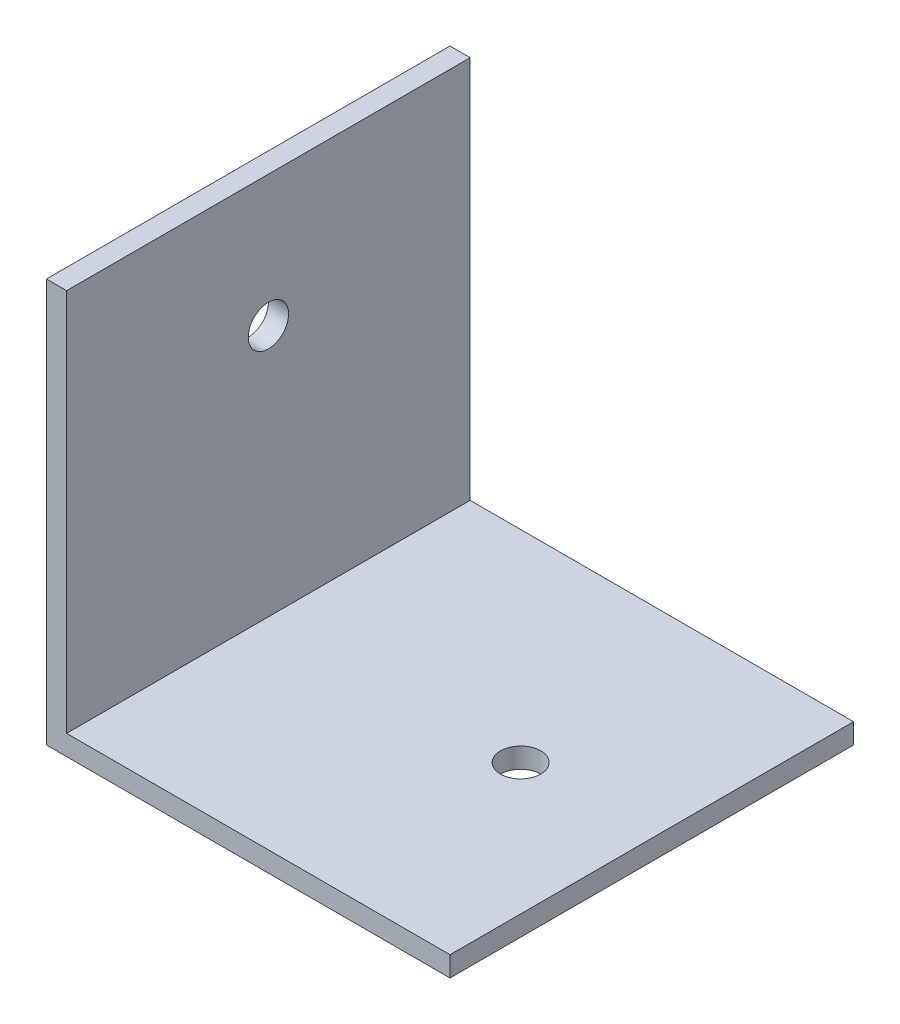
SolidWorks part; units mm, degrees
ref_plane "Plan de face" through (0, 0, 0) normal (0, 0, 1) x (1, 0, 0)
ref_plane "Plan de dessus" through (0, 0, 0) normal (0, 1, 0) x (1, 0, 0)
ref_plane "Plan de droite" through (0, 0, 0) normal (1, 0, 0) x (0, 0, -1)
sketch "Esquisse1" plane through (0, 0, 0) normal (0, 0, 1) x (1, 0, 0)
  line L0 (0, 0) -> (20, 0)
  line L1 (0, 0) -> (0, 20)
  dimension "D1" = 20
  dimension "D2" = 20
extrude "Extru.-Mince1" add sketch "Esquisse1" along normal blind 20 thin thin type one direction wall 1
sketch "Esquisse2" plane through (1, 0, 0) normal (1, 0, 0) x (0, 0, -1)
  line L0 (0, 1) -> (0, 20) construction
  line L1 (-20, 20) -> (0, 20) construction
  circle A0 centre (-10, 13.5) radius 1
  dimension "D3" = 2
  dimension "D1" = 10
  dimension "D2" = 6.5
extrude "Enlèv. mat.-Extru.1" cut sketch "Esquisse2" against normal blind 1
sketch "Esquisse3" plane through (0, 1, 0) normal (0, 1, 0) x (1, 0, 0)
  line L0 (20, 0) -> (1, 0) construction
  line L1 (20, -20) -> (20, 0) construction
  circle A0 centre (13.5, -10) radius 1
  dimension "D1" = 2
  dimension "D2" = 10
  dimension "D3" = 6.5
extrude "Enlèv. mat.-Extru.2" cut sketch "Esquisse3" against normal blind 1
